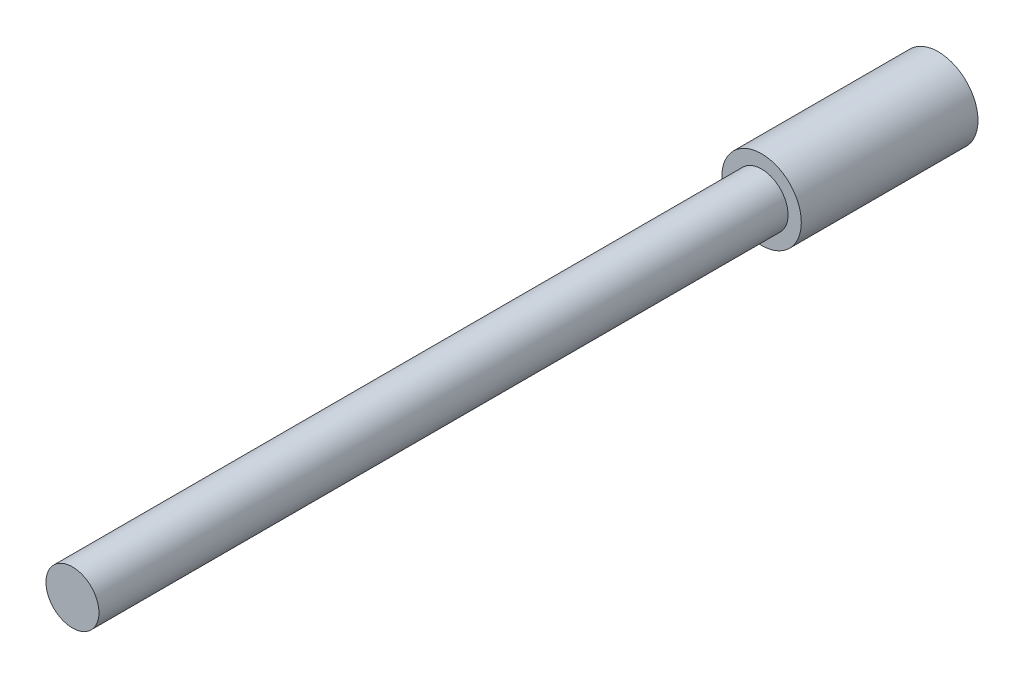
SolidWorks part; units mm, degrees
material "Aluminum"
ref_plane "Front Plane" through (0, 0, 0) normal (0, 0, 1) x (1, 0, 0)
ref_plane "Top Plane" through (0, 0, 0) normal (0, 1, 0) x (1, 0, 0)
ref_plane "Right Plane" through (0, 0, 0) normal (1, 0, 0) x (0, 0, -1)
sketch "Sketch1" plane through (0, 0, 0) normal (0, 0, 1) x (1, 0, 0)
  circle A0 centre (0, 0) radius 2.25
  dimension "D1" = 4.5
extrude "Boss-Extrude1" add sketch "Sketch1" along normal blind 10
sketch "Sketch2" plane through (0, 0, 10) normal (0, 0, 1) x (1, 0, 0)
  circle A0 centre (0, 0) radius 1.5
  dimension "D1" = 3
extrude "Boss-Extrude2" add sketch "Sketch2" along normal blind 39
sketch "Sketch3" plane through (0, 0, 0) normal (0, 0, -1) x (-1, 0, 0)
  circle A0 centre (0, 0) radius 1.5
  dimension "D1" = 3
extrude "Cut-Extrude1" cut sketch "Sketch3" against normal blind 4.5
